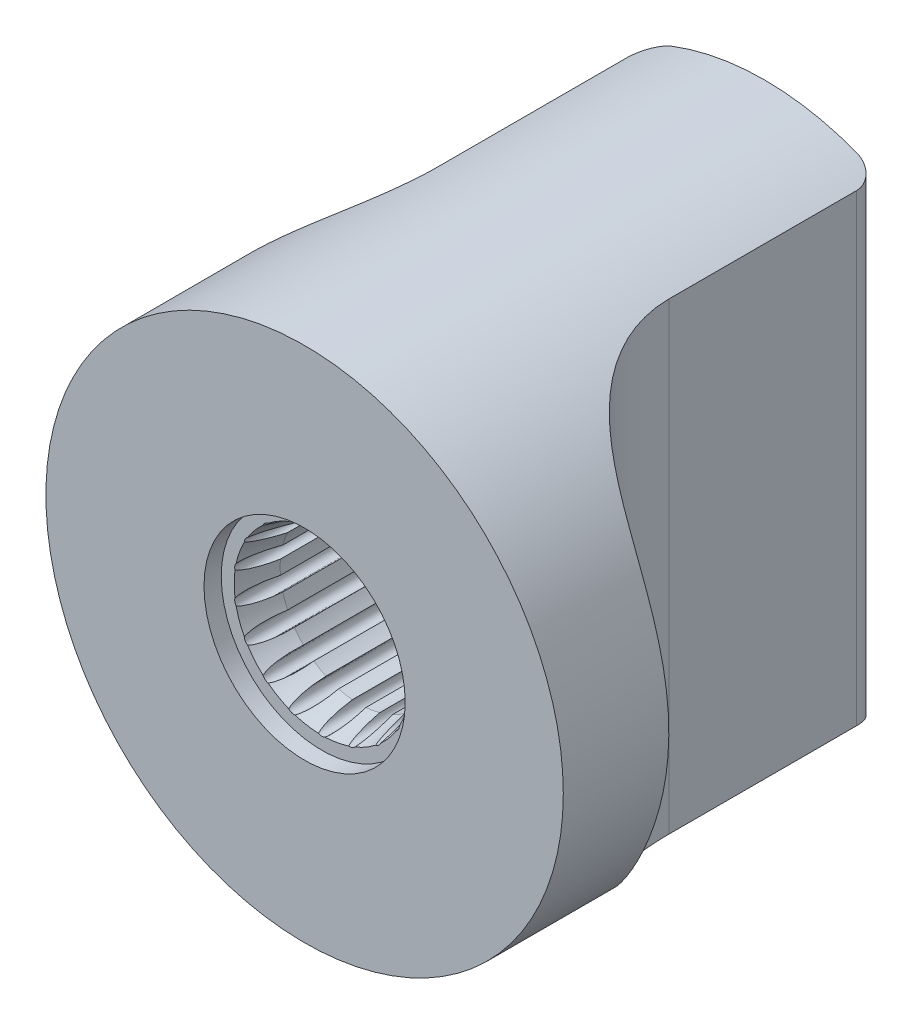
SolidWorks part; units mm, degrees
ref_plane "Front Plane" through (0, 0, 0) normal (0, 0, 1) x (1, 0, 0)
ref_plane "Top Plane" through (0, 0, 0) normal (0, 1, 0) x (1, 0, 0)
ref_plane "Right Plane" through (0, 0, 0) normal (1, 0, 0) x (0, 0, -1)
sketch "Sketch1" plane through (0, 0, 0) normal (0, 0, 1) x (1, 0, 0)
  circle A0 centre (0, 0) radius 9
  dimension "D1" = 18
extrude "Boss-Extrude1" add sketch "Sketch1" along normal blind 16
sketch "Sketch2" plane through (0, 0, 0) normal (0, 1, 0) x (1, 0, 0)
  line L0 (4, 0) -> (-4, 0)
  line L1 (9, 0) -> (-9, 0) construction
  line L2 (4, 0) -> (4, -7.3288)
  line L3 (0, 0) -> (0, -16) construction
  line L4 (9, -16) -> (9, 0) construction
  line L5 (9, -12.3288) -> (9, -16)
  line L6 (9, -16) -> (-9, -16)
  line L7 (-9, -16) -> (9, -16) construction
  line L8 (-9, -12.3288) -> (-9, -16)
  line L9 (-4, 0) -> (-4, -7.3288)
  line L10 (-9, 0) -> (-9, -16) construction
  line L11 (9, -12.3288) -> (-9, -12.3288) construction
  arc A0 (4, -7.3288) -> (9, -12.3288) centre (9, -7.3288) ccw
  arc A1 (-4, -7.3288) -> (-9, -12.3288) centre (-9, -7.3288) cw
  point P3 (0, 0)
  point P6 (0, 0)
  dimension "D1" = 8
extrude "Perfil lateral" cut sketch "Sketch2" against normal through all both and the other way through all flip side to cut
sketch "Sketch3" plane through (0, 0, 16) normal (0, 0, 1) x (1, 0, 0)
  line L0 (0, 0) -> (0, 6.2989) construction
  line L1 (0, 0) -> (0, 2.75) construction
  arc A1 (-1.9413, 1.9478) -> (-2.2553, 1.5736) centre (0, 0) ccw
  arc A2 (0.2351, 2.7399) -> (-0.2351, 2.7399) centre (0, 2.825) ccw
  arc A3 (1.158, 2.4943) -> (0.7162, 2.6551) centre (0.9662, 2.6546) ccw
  arc A4 (1.9413, 1.9478) -> (1.5811, 2.25) centre (1.8159, 2.1641) ccw
  arc A5 (2.4904, 1.1664) -> (2.2553, 1.5736) centre (2.4465, 1.4125) ccw
  arc A6 (2.7391, 0.2443) -> (2.6575, 0.7073) centre (2.7821, 0.4906) ccw
  arc A7 (2.6575, -0.7073) -> (2.7391, -0.2443) centre (2.7821, -0.4906) ccw
  arc A8 (2.2553, -1.5736) -> (2.4904, -1.1664) centre (2.4465, -1.4125) ccw
  arc A9 (1.5811, -2.25) -> (1.9413, -1.9478) centre (1.8159, -2.1641) ccw
  arc A10 (0.7162, -2.6551) -> (1.158, -2.4943) centre (0.9662, -2.6546) ccw
  arc A11 (-0.2351, -2.7399) -> (0.2351, -2.7399) centre (0, -2.825) ccw
  arc A12 (-1.158, -2.4943) -> (-0.7162, -2.6551) centre (-0.9662, -2.6546) ccw
  arc A13 (-1.9413, -1.9478) -> (-1.5811, -2.25) centre (-1.8159, -2.1641) ccw
  arc A14 (-2.4904, -1.1664) -> (-2.2553, -1.5736) centre (-2.4465, -1.4125) ccw
  arc A15 (-2.7391, -0.2443) -> (-2.6575, -0.7073) centre (-2.7821, -0.4906) ccw
  arc A16 (-2.6575, 0.7073) -> (-2.7391, 0.2443) centre (-2.7821, 0.4906) ccw
  arc A17 (-2.2553, 1.5736) -> (-2.4904, 1.1664) centre (-2.4465, 1.4125) ccw
  arc A18 (-1.5811, 2.25) -> (-1.9413, 1.9478) centre (-1.8159, 2.1641) ccw
  arc A19 (-0.7162, 2.6551) -> (-1.158, 2.4943) centre (-0.9662, 2.6546) ccw
  arc A20 (-1.158, 2.4943) -> (-1.5811, 2.25) centre (0, 0) ccw
  arc A21 (-0.2351, 2.7399) -> (-0.7162, 2.6551) centre (0, 0) ccw
  arc A22 (0.7162, 2.6551) -> (0.2351, 2.7399) centre (0, 0) ccw
  arc A23 (1.5811, 2.25) -> (1.158, 2.4943) centre (0, 0) ccw
  arc A24 (2.2553, 1.5736) -> (1.9413, 1.9478) centre (0, 0) ccw
  arc A25 (2.6575, 0.7073) -> (2.4904, 1.1664) centre (0, 0) ccw
  arc A26 (2.7391, -0.2443) -> (2.7391, 0.2443) centre (0, 0) ccw
  arc A27 (2.4904, -1.1664) -> (2.6575, -0.7073) centre (0, 0) ccw
  arc A28 (1.9413, -1.9478) -> (2.2553, -1.5736) centre (0, 0) ccw
  arc A29 (1.158, -2.4943) -> (1.5811, -2.25) centre (0, 0) ccw
  arc A30 (0.2351, -2.7399) -> (0.7162, -2.6551) centre (0, 0) ccw
  arc A31 (-0.7162, -2.6551) -> (-0.2351, -2.7399) centre (0, 0) ccw
  arc A32 (-1.5811, -2.25) -> (-1.158, -2.4943) centre (0, 0) ccw
  arc A33 (-2.2553, -1.5736) -> (-1.9413, -1.9478) centre (0, 0) ccw
  arc A34 (-2.6575, -0.7073) -> (-2.4904, -1.1664) centre (0, 0) ccw
  arc A35 (-2.7391, 0.2443) -> (-2.7391, -0.2443) centre (0, 0) ccw
  arc A36 (-2.4904, 1.1664) -> (-2.6575, 0.7073) centre (0, 0) ccw
  point P43 (0, 3.075)
  point P60 (0, -3.075)
  dimension "D1" = 5.5
  dimension "D3" = 0.5
  dimension "D2" = 2.825
  dimension "D4" = 3.075
  dimension "D5" = 6.15
extrude "Hueco ppal" cut sketch "Sketch3" against normal blind 10.5
sketch "Sketch4" plane through (0, 0, 16) normal (0, 0, 1) x (1, 0, 0)
  circle A0 centre (0, 0) radius 3.5
  dimension "D1" = 7
extrude "Cut-Extrude4" cut sketch "Sketch4" against normal blind 0.6
chamfer "Chamfer1" distance 0.3 angle 77 18 edges at (-2.5842, 0.9406, 15.4) (-2.75, 0, 15.4) (-2.5842, -0.9406, 15.4) (-2.1066, -1.7677, 15.4) (-1.375, -2.3816, 15.4) (-0.4775, -2.7082, 15.4) (0.4775, -2.7082, 15.4) (1.375, -2.3816, 15.4) (2.1066, -1.7677, 15.4) (2.5842, -0.9406, 15.4) (2.75, 0, 15.4) (2.5842, 0.9406, 15.4) (2.1066, 1.7677, 15.4) (1.375, 2.3816, 15.4) (0.4775, 2.7082, 15.4) (-0.4775, 2.7082, 15.4) (-1.375, 2.3816, 15.4) (-2.1066, 1.7677, 15.4)
fillet "Fillet1" radius 0.8 2 edges at (4, 0, 0) (-4, 0, 0)
